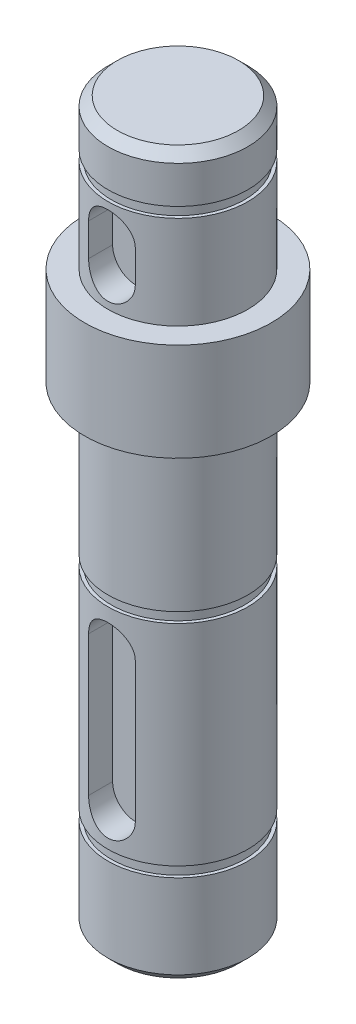
SolidWorks part; units mm, degrees
material "3.1325 (EN-AW 2017A)"
ref_plane "Płaszczyzna przednia" through (0, 0, 0) normal (0, 0, 1) x (1, 0, 0)
ref_plane "Płaszczyzna górna" through (0, 0, 0) normal (0, 1, 0) x (1, 0, 0)
ref_plane "Płaszczyzna prawa" through (0, 0, 0) normal (1, 0, 0) x (0, 0, -1)
sketch "Szkic1" plane through (0, 0, 0) normal (0, 0, 1) x (1, 0, 0)
  line L0 (0, 0) -> (0, 71.0179) construction
  line L1 (0, 0) -> (-7.5, 0)
  line L2 (-7.5, 0) -> (-7.5, 10)
  line L3 (-7.5, 10) -> (-7.15, 10)
  line L4 (-7.15, 10) -> (-7.15, 11.1)
  line L5 (-7.15, 11.1) -> (-7.5, 11.1)
  line L6 (-7.5, 11.1) -> (-7.5, 33.6)
  line L7 (-7.5, 33.6) -> (-7.15, 33.6)
  line L8 (-7.15, 33.6) -> (-7.15, 34.7)
  line L9 (-7.15, 34.7) -> (-7.5, 34.7)
  line L10 (-7.5, 34.7) -> (-7.5, 50.7)
  line L11 (-7.5, 50.7) -> (-10, 50.7)
  line L12 (-10, 50.7) -> (-10, 61.2)
  line L13 (-10, 61.2) -> (-7.5, 61.2)
  line L14 (-7.5, 61.2) -> (-7.5, 71.2)
  line L15 (-7.5, 71.2) -> (-7.15, 71.2)
  line L16 (-7.15, 71.2) -> (-7.15, 72.3)
  line L17 (-7.15, 72.3) -> (-7.5, 72.3)
  line L18 (-7.5, 72.3) -> (-7.5, 77.3)
  line L19 (-7.5, 77.3) -> (0, 77.3)
  line L20 (0, 0) -> (0, 77.3)
  dimension "D1" = 7.5
  dimension "D2" = 0.35
  dimension "D3" = 1.1
  dimension "D4" = 7.5
  dimension "D5" = 7.5
  dimension "D6" = 10
  dimension "D7" = 22.5
  dimension "D8" = 1.1
  dimension "D9" = 0.35
  dimension "D10" = 16
  dimension "D11" = 10
  dimension "D12" = 10
  dimension "D13" = 0.35
  dimension "D14" = 1.1
revolve "Obrót1" add sketch "Szkic1" angle 360 about L0
chamfer "Sfazowanie1" distance 1 angle 45 2 edges at (0, 77.3, -7.5) (0, 0, -7.5)
ref_plane "Płaszczyzna1" through (0, 0, 7.5) normal (0, 0, 1) x (1, 0, 0)
sketch "Szkic2" plane through (0, 0, 7.5) normal (0, 0, 1) x (1, 0, 0)
  line L0 (0, 77.3) -> (0, 0) construction
  line L1 (6.5, 77.3) -> (-6.5, 77.3) construction
  line L2 (-7.5, 66.2) -> (7.5, 66.2) construction
  line L3 (-7.5, 71.2) -> (-7.5, 61.2) construction
  line L4 (7.5, 61.2) -> (7.5, 71.2) construction
  line L5 (-7.5, 22.35) -> (7.5, 22.35) construction
  line L6 (-7.5, 33.6) -> (-7.5, 11.1) construction
  line L7 (7.5, 11.1) -> (7.5, 33.6) construction
  line L8 (0, 14.6377) -> (0, 29.6377) construction
  line L9 (-2.5, 14.6377) -> (-2.5, 29.6377)
  line L10 (2.5, 14.6377) -> (2.5, 29.6377)
  line L11 (0, 64.45) -> (0, 67.95) construction
  line L12 (-2.5, 64.45) -> (-2.5, 67.95)
  line L13 (2.5, 64.45) -> (2.5, 67.95)
  arc A0 (-2.5, 14.6377) -> (2.5, 14.6377) centre (0, 14.6377) ccw
  arc A1 (2.5, 29.6377) -> (-2.5, 29.6377) centre (0, 29.6377) ccw
  arc A2 (-2.5, 64.45) -> (2.5, 64.45) centre (0, 64.45) ccw
  arc A3 (2.5, 67.95) -> (-2.5, 67.95) centre (0, 67.95) ccw
  point P19 (0, 22.1377)
  point P26 (0, 66.2)
  dimension "D1" = 15
  dimension "D2" = 5
  dimension "D3" = 5
  dimension "D4" = 3.5
extrude "Wytnij-wyciągnięcie1" cut sketch "Szkic2" against normal blind 3
